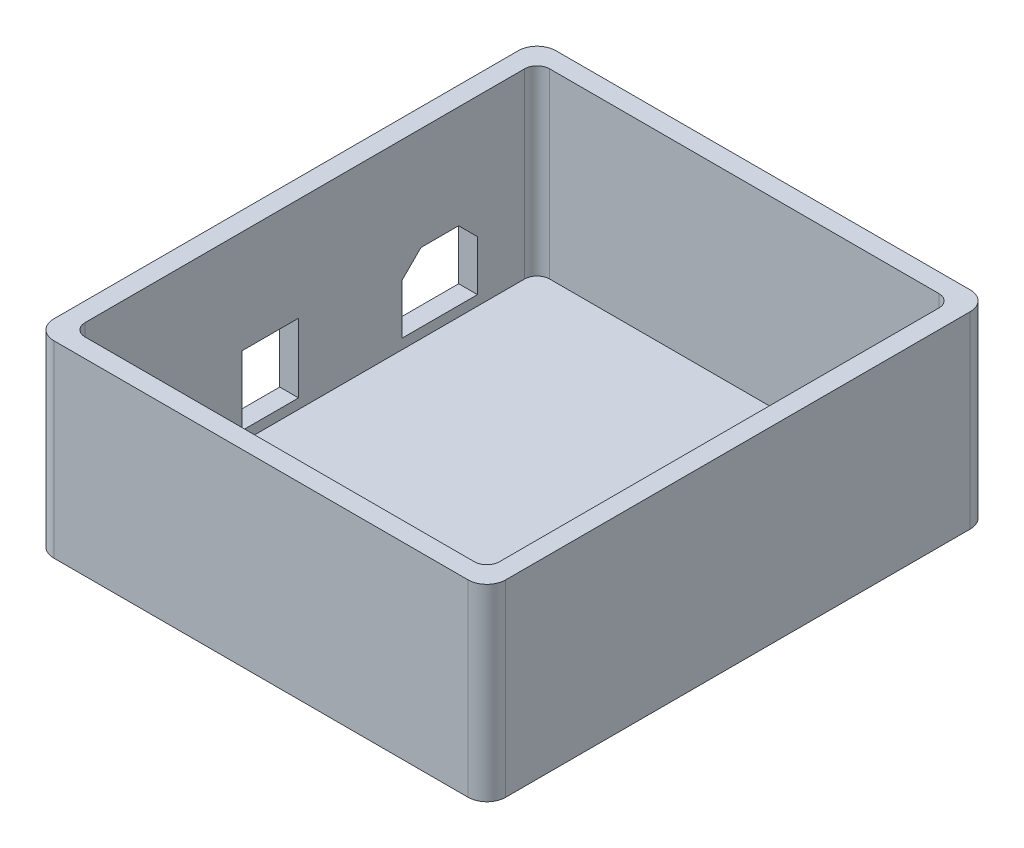
SolidWorks part; units mm, degrees
ref_plane "Front Plane" through (0, 0, 0) normal (0, 0, 1) x (1, 0, 0)
ref_plane "Top Plane" through (0, 0, 0) normal (0, 1, 0) x (1, 0, 0)
ref_plane "Right Plane" through (0, 0, 0) normal (1, 0, 0) x (0, 0, -1)
sketch "Sketch2" plane through (0, 0, 0) normal (0, 1, 0) x (1, 0, 0)
  line L1 (-36.9773, 28.5552) -> (29.0227, 28.5552)
  line L2 (-39.9773, 25.5552) -> (-39.9773, -48.4448)
  line L3 (-36.9773, -51.4448) -> (29.0227, -51.4448)
  line L4 (32.0227, 25.5552) -> (32.0227, -48.4448)
  arc A0 (-39.9773, -48.4448) -> (-36.9773, -51.4448) centre (-36.9773, -48.4448) ccw
  arc A1 (29.0227, -51.4448) -> (32.0227, -48.4448) centre (29.0227, -48.4448) ccw
  arc A2 (29.0227, 28.5552) -> (32.0227, 25.5552) centre (29.0227, 25.5552) cw
  arc A3 (-36.9773, 28.5552) -> (-39.9773, 25.5552) centre (-36.9773, 25.5552) ccw
  point P8 (32.0227, -51.4448)
  point P11 (32.0227, 28.5552)
  point P14 (-39.9773, 28.5552)
  dimension "D3" = 3
  dimension "D1" = 72
  dimension "D2" = 80
extrude "Boss-Extrude1" add sketch "Sketch2" along normal blind 30
sketch "Sketch3" plane through (0, 30, 0) normal (0, 1, 0) x (1, 0, 0)
  line L1 (-34.9773, 25.5552) -> (27.0227, 25.5552)
  line L2 (-36.9773, 23.5552) -> (-36.9773, -46.4448)
  line L3 (-34.9773, -48.4448) -> (27.0227, -48.4448)
  line L4 (29.0227, 23.5552) -> (29.0227, -46.4448)
  arc A0 (-36.9773, -46.4448) -> (-34.9773, -48.4448) centre (-34.9773, -46.4448) ccw
  arc A1 (27.0227, -48.4448) -> (29.0227, -46.4448) centre (27.0227, -46.4448) ccw
  arc A2 (27.0227, 25.5552) -> (29.0227, 23.5552) centre (27.0227, 23.5552) cw
  arc A3 (-34.9773, 25.5552) -> (-36.9773, 23.5552) centre (-34.9773, 23.5552) ccw
  point P10 (29.0227, -48.4448)
  point P15 (-36.9773, 25.5552)
  dimension "D1" = 2
extrude "Cut-Extrude1" cut sketch "Sketch3" against normal blind 29
sketch "Sketch5" plane through (-39.9773, 0, 0) normal (-1, 0, 0) x (0, 0, 1)
  line L4 (6.1099, 14.3912) -> (17.1099, 14.3912)
  line L5 (6.1099, 14.3912) -> (6.1099, 2.3912)
  line L6 (6.1099, 2.3912) -> (17.1099, 2.3912)
  line L7 (17.1099, 14.3912) -> (17.1099, 2.3912)
  line L9 (9.1099, 14.3912) -> (6.1099, 11.395)
  line L10 (14.1099, 14.3912) -> (17.1099, 11.395)
  dimension "D1" = 11
  dimension "D2" = 12
  dimension "D3" = 4.24
  dimension "D4" = 4.24
  dimension "D5" = 3
  dimension "D6" = 3
extrude "Cut-Extrude3" cut sketch "Sketch5" against normal blind 10 contours L10 L4 L9 L5 L6 L7
sketch "Sketch6" plane through (-39.9773, 0, 0) normal (-1, 0, 0) x (0, 0, 1)
  line L1 (-1.7356, 17.7795) -> (25.3803, 17.7795)
  line L2 (-1.7356, 17.7795) -> (-1.7356, 1.1768)
  line L3 (-1.7356, 1.1768) -> (25.3803, 1.1768)
  line L4 (25.3803, 17.7795) -> (25.3803, 1.1768)
extrude "Boss-Extrude2" add sketch "Sketch6" against normal blind 3
sketch "Sketch7" plane through (0, 0, 51.4448) normal (0, 0, 1) x (1, 0, 0)
  line L0 (-29.1545, 10.4034) -> (-26.1065, 13.462)
  line L1 (-26.1065, 13.462) -> (-20.2751, 13.462)
  line L2 (-20.2751, 13.462) -> (-17.2165, 10.414)
  line L3 (-17.2165, 10.414) -> (-17.2165, 2.54)
  line L4 (-29.1545, 10.4034) -> (-29.1545, 2.54)
  line L5 (-29.1545, 2.54) -> (-17.2165, 2.54)
  line L7 (14.9728, 13.462) -> (23.8628, 13.462)
  line L8 (14.9728, 13.462) -> (14.9728, 2.54)
  line L9 (14.9728, 2.54) -> (23.8628, 2.54)
  line L10 (23.8628, 13.462) -> (23.8628, 2.54)
  line L11 (-36.9773, 0) -> (29.0227, 0) construction
  dimension "D1" = 11.938
  dimension "D2" = 4.318
  dimension "D3" = 4.318
  dimension "D4" = 10.922
  dimension "D5" = 8.89
  dimension "D6" = 7.874
  dimension "D7" = 10.922
  dimension "D8" = 2.54
  dimension "D9" = 2.54
extrude "Cut-Extrude4" cut sketch "Sketch7" against normal blind 6350
sketch "Sketch8" plane through (0, 0, -28.5552) normal (0, 0, -1) x (-1, 0, 0)
  line L0 (20.2751, 13.462) -> (17.2165, 10.414)
  line L1 (-23.8628, 13.462) -> (-14.9728, 13.462)
  line L2 (-23.8628, 13.462) -> (-23.8628, 2.54)
  line L3 (-23.8628, 2.54) -> (-14.9728, 2.54)
  line L4 (-14.9728, 13.462) -> (-14.9728, 2.54)
  line L5 (17.2165, 10.414) -> (17.2165, 2.54)
  line L6 (17.2165, 2.54) -> (17.2165, 10.414) construction
  line L7 (29.1545, 2.54) -> (17.2165, 2.54) construction
  line L8 (17.2165, 2.54) -> (29.1545, 2.54)
  line L9 (29.1545, 2.54) -> (29.1545, 10.0992)
  line L10 (29.1545, 10.4034) -> (29.1545, 2.54) construction
  line L11 (29.1545, 10.4034) -> (26.1065, 13.462)
  line L12 (26.1065, 13.462) -> (29.1545, 10.4034) construction
  line L13 (26.1065, 13.462) -> (20.3831, 13.462)
  line L14 (20.2751, 13.462) -> (26.1065, 13.462) construction
  line M1 (26.1065, 13.462) -> (29.1545, 10.4034)
  line M2 (29.1545, 10.4034) -> (29.1545, 2.54)
  line M3 (29.1545, 2.54) -> (17.2165, 2.54)
  line M4 (17.2165, 2.54) -> (17.2165, 10.414)
  line M5 (17.2165, 10.414) -> (20.2751, 13.462)
  line M6 (20.2751, 13.462) -> (26.1065, 13.462)
  line M7 (-23.8628, 13.462) -> (-14.9728, 13.462)
  line M8 (-14.9728, 13.462) -> (-14.9728, 2.54)
  line M9 (-14.9728, 2.54) -> (-23.8628, 2.54)
  line M10 (-23.8628, 2.54) -> (-23.8628, 13.462)
extrude "Boss-Extrude3" add sketch "Sketch8" against normal up to vertex contours M7 M10 M9 M8 | M1 M6 M5 M4 M3 M2
sketch "Sketch9" plane through (0, 0, 51.4448) normal (0, 0, 1) x (1, 0, 0)
  line L0 (-29.1545, 2.54) -> (-17.2165, 2.54)
  line L1 (14.9728, 13.462) -> (23.8628, 13.462)
  line L2 (14.9728, 13.462) -> (14.9728, 2.54)
  line L3 (14.9728, 2.54) -> (23.8628, 2.54)
  line L4 (23.8628, 13.462) -> (23.8628, 2.54)
  line L5 (-17.2165, 2.54) -> (-17.2165, 10.414)
  line L6 (-17.2165, 10.414) -> (-20.2751, 13.462)
  line L7 (-20.2751, 13.462) -> (-26.1065, 13.462)
  line L8 (-26.1065, 13.462) -> (-29.1545, 10.4034)
  line L9 (-29.1545, 10.4034) -> (-29.1545, 2.54)
extrude "Boss-Extrude4" add sketch "Sketch9" against normal up to vertex
sketch "Sketch12" plane through (-39.9773, 0, 0) normal (-1, 0, 0) x (0, 0, 1)
  line L2 (-16.0552, 10.6) -> (-16.0552, 2.6)
  line L3 (-16.0552, 2.6) -> (-4.0552, 2.6)
  line L4 (-4.0552, 2.6) -> (-4.0552, 10.6)
  line L5 (-4.0552, 10.6) -> (-7.0552, 13.5963)
  line L6 (-7.0552, 13.5963) -> (-13.0552, 13.5963)
  line L7 (-13.0552, 13.5963) -> (-16.0552, 10.6)
  line L10 (12.4448, 13.6) -> (21.4448, 13.6)
  line L11 (12.4448, 13.6) -> (12.4448, 2.6)
  line L12 (12.4448, 2.6) -> (21.4448, 2.6)
  line L13 (21.4448, 13.6) -> (21.4448, 2.6)
  line L14 (-25.5552, 0) -> (48.4448, 0) construction
  dimension "D1" = 8
  dimension "D2" = 12
  dimension "D3" = 8
  dimension "D4" = 6
  dimension "D5" = 4.24
  dimension "D6" = 4.24
  dimension "D7" = 2.6
  dimension "D8" = 9
  dimension "D9" = 11
  dimension "D11" = 9
  dimension "D12" = 2.6
  dimension "D13" = 2.6
extrude "Cut-Extrude6" cut sketch "Sketch12" against normal blind 3
sketch "Sketch13" plane through (29.0227, 0, 0) normal (-1, 0, 0) x (0, 0, 1)
  line L0 (51.4448, 30) -> (51.4448, 0) construction
  line L1 (51.4448, 29.8957) -> (-28.5552, 29.8957)
  line L2 (51.4448, 29.8957) -> (51.4448, 0)
  line L3 (51.4448, 0) -> (-28.5552, 0)
  line L4 (-28.5552, 29.8957) -> (-28.5552, 0)
